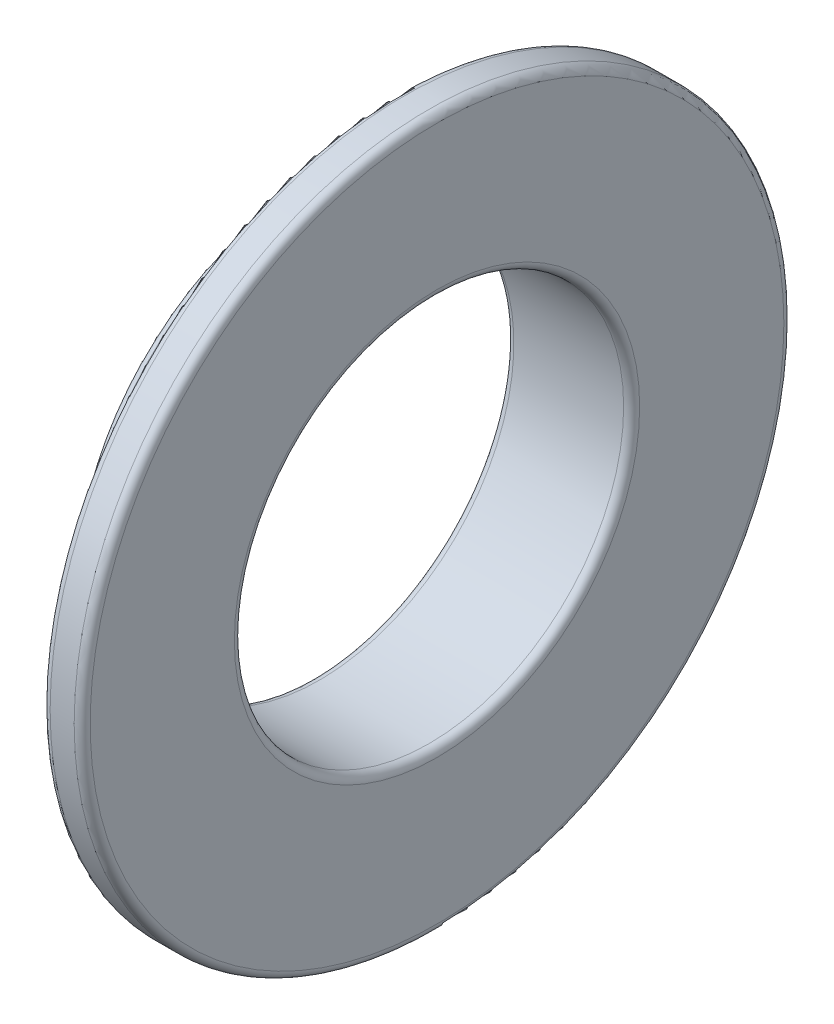
SolidWorks part; units mm, degrees
ref_plane "Front Plane" through (0, 0, 0) normal (0, 0, 1) x (1, 0, 0)
ref_plane "Top Plane" through (0, 0, 0) normal (0, 1, 0) x (1, 0, 0)
ref_plane "Right Plane" through (0, 0, 0) normal (1, 0, 0) x (0, 0, -1)
sketch "Sketch1" plane through (0, 0, 0) normal (0, 0, 1) x (1, 0, 0)
  line L0 (-30.8496, 0) -> (-13.9977, 0) construction
  line L1 (-12.5, 22.15) -> (-12.5, 12.15) construction
  line L2 (-12.5, 12.15) -> (-4.65, 12.15) construction
  line L3 (-4.65, 12.15) -> (-4.65, 15.15) construction
  line L4 (-4.65, 15.15) -> (9.8, 15.15) construction
  line L5 (9.8, 15.15) -> (9.8, 17.15) construction
  line L6 (9.8, 17.15) -> (-10, 17.15) construction
  line L7 (-10, 17.15) -> (-10, 22.15) construction
  line L8 (-10, 22.15) -> (-12.5, 22.15) construction
  line L9 (10, 22.15) -> (12.5, 22.15)
  line L10 (12.5, 22.15) -> (12.5, 12.15)
  line L11 (12.5, 12.15) -> (4.65, 12.15)
  line L12 (4.65, 12.15) -> (4.65, 15.15)
  line L13 (4.65, 15.15) -> (9.8, 15.15) construction
  line L14 (9.8, 15.15) -> (9.8, 17.15) construction
  line L15 (9.8, 17.15) -> (10, 17.15) construction
  line L16 (10, 17.15) -> (10, 22.15)
  line L17 (-4.65, 12.15) -> (4.65, 12.15) construction
  line L18 (-10, 22.15) -> (10, 22.15) construction
  line L19 (0, 0) -> (0, 12.15) construction
  line L20 (0, 22.15) -> (0, 12.15) construction
  line L21 (4.65, 14.95) -> (10, 14.95)
  line L22 (10, 14.95) -> (10, 17.15)
  dimension "D1" = 20
  dimension "D2" = 2.5
  dimension "D3" = 15.15
  dimension "D4" = 3
  dimension "D5" = 2
  dimension "D6" = 5
  dimension "D7" = 0.2
  dimension "D8" = 9.3
  dimension "D9" = 0.2
revolve "Revolve1" add sketch "Sketch1" angle 360 about L0
fillet "Fillet1" radius 0.5 6 edges at (12.5, 0, 22.15) (4.65, 0, 14.95) (10, 0, 14.95) (10, 0, 22.15) (12.5, 0, 12.15) (4.65, 0, 12.15)
